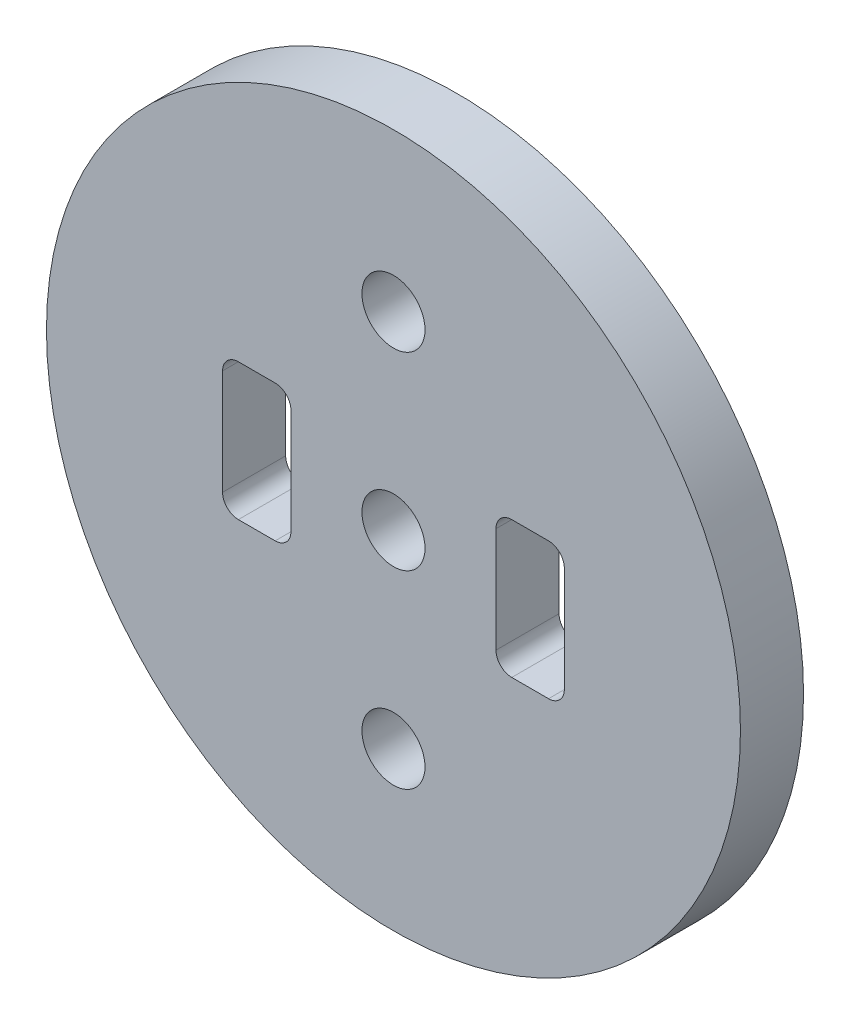
SolidWorks part; units mm, degrees
ref_plane "Alzado" through (0, 0, 0) normal (0, 0, 1) x (1, 0, 0)
ref_plane "Planta" through (0, 0, 0) normal (0, 1, 0) x (1, 0, 0)
ref_plane "Vista lateral" through (0, 0, 0) normal (1, 0, 0) x (0, 0, -1)
sketch "Model" plane through (0, 0, 0) normal (0, 0, 1) x (1, 0, 0)
  line L0 (223.1228, 245.202) -> (221.3728, 245.202)
  line L1 (223.8728, 239.452) -> (223.8728, 244.452)
  line L2 (221.3728, 238.702) -> (223.1228, 238.702)
  line L3 (220.6228, 244.452) -> (220.6228, 239.452)
  line L4 (208.3728, 245.202) -> (210.1228, 245.202)
  line L5 (207.6228, 239.452) -> (207.6228, 244.452)
  line L6 (210.1228, 238.702) -> (208.3728, 238.702)
  line L7 (210.8728, 244.452) -> (210.8728, 239.452)
  circle A0 centre (215.7478, 241.952) radius 1.5
  circle A1 centre (215.7478, 232.952) radius 1.5
  circle A2 centre (215.7478, 250.952) radius 1.5
  arc A3 (221.3728, 245.202) -> (220.6228, 244.452) centre (221.3728, 244.452) ccw
  arc A4 (223.8728, 244.452) -> (223.1228, 245.202) centre (223.1228, 244.452) ccw
  arc A5 (223.1228, 238.702) -> (223.8728, 239.452) centre (223.1228, 239.452) ccw
  arc A6 (220.6228, 239.452) -> (221.3728, 238.702) centre (221.3728, 239.452) ccw
  arc A7 (210.8728, 244.452) -> (210.1228, 245.202) centre (210.1228, 244.452) ccw
  arc A8 (208.3728, 245.202) -> (207.6228, 244.452) centre (208.3728, 244.452) ccw
  arc A9 (207.6228, 239.452) -> (208.3728, 238.702) centre (208.3728, 239.452) ccw
  arc A10 (210.1228, 238.702) -> (210.8728, 239.452) centre (210.1228, 239.452) ccw
  circle A11 centre (215.7478, 241.952) radius 16.5
extrude "Saliente-Extruir1" add sketch "Model" along normal blind 3
